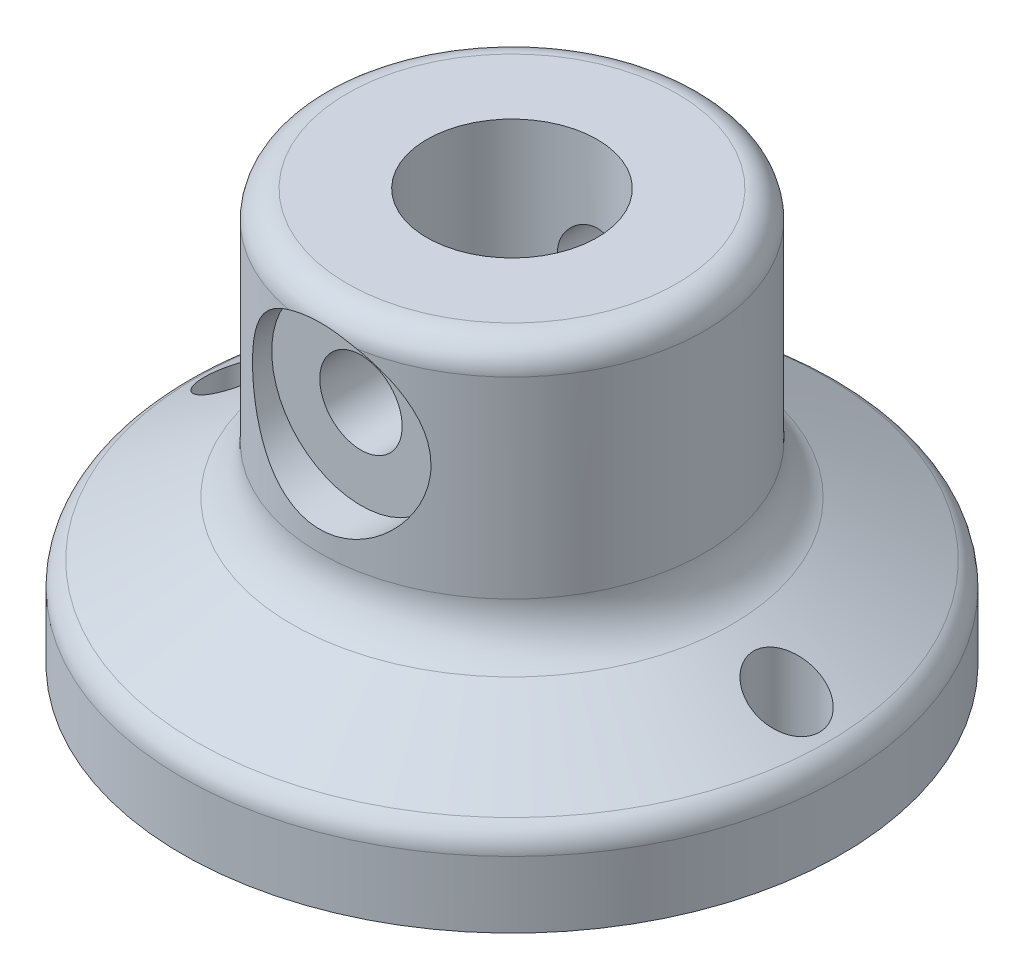
SolidWorks part; units mm, degrees
material "ABS"
ref_plane "Plan de face" through (0, 0, 0) normal (0, 0, 1) x (1, 0, 0)
ref_plane "Plan de dessus" through (0, 0, 0) normal (0, 1, 0) x (1, 0, 0)
ref_plane "Plan de droite" through (0, 0, 0) normal (1, 0, 0) x (0, 0, -1)
sketch "Esquisse1" plane through (0, 0, 0) normal (0, 0, 1) x (1, 0, 0)
  line L0 (0, 0) -> (0, 15) construction
  line L2 (3.1, 15) -> (3.1, 1)
  line L3 (4, 0) -> (12, 0)
  line L4 (12, 0) -> (12, 3)
  line L5 (12, 3) -> (8.0136, 5.2602)
  line L6 (7, 7) -> (7, 15)
  line L7 (7, 15) -> (3.1, 15)
  line L10 (3.1, 1) -> (4, 1)
  line L11 (4, 0) -> (4, 1)
  arc A0 (8.0136, 5.2602) -> (7, 7) centre (9, 7) cw
  dimension "D1" = 6.2
  dimension "D6" = 2
  dimension "D2" = 3
  dimension "D3" = 24
  dimension "D4" = 8
  dimension "D5" = 15
  dimension "D7" = 14
  dimension "D8" = 8
  dimension "D9" = 1
revolve "Révolution1" add sketch "Esquisse1" angle 360 about L0
fillet "Congé1" radius 1 2 edges at (0, 3, -12) (0, 15, -7)
sketch "Esquisse2" plane through (0, 0, 0) normal (0, -1, 0) x (1, 0, 0)
  line L0 (-10, 0) -> (10, 0) construction
  circle A0 centre (-10, 0) radius 1.2
  circle A1 centre (10, 0) radius 1.2
  dimension "D1" = 20
  dimension "D2" = 2.4
extrude "Enlèv. mat.-Extru.1" cut sketch "Esquisse2" against normal through all
hole_wizard "Chambrage pour vis à tête cylindrique à 6 pans creux (ou vis CHC) M31" positions "Esquisse3D1" profile "Esquisse5" counterbore size "M3" standard "Ansi Metric" end condition through all
sketch3d "Esquisse3D1"
  point P0 (0, 11, 7)
  dimension "D1" = 4
sketch "Esquisse5" plane through (0, 11, 7) normal (1, 0, 0) x (0, -1, 0)
  line L0 (0, 0) -> (0, 19)
  line L1 (0, 19) -> (1.2, 19)
  line L3 (1.2, 19) -> (1.2, 1.5)
  line L4 (1.2, 1.5) -> (3.25, 1.5)
  line L5 (3.25, 1.5) -> (3.25, 0)
  line L7 (3.25, 0) -> (0, 0)
  line L11 (0, -6.35) -> (0, 107.95) construction
  dimension "Diamètre du perçage jusqu'au prochain" = 2.4
  dimension "Profondeur du perçage jusqu'au prochain" = 19
  dimension "Diamètre du chambrage" = 6.5
  dimension "Profondeur du chambrage" = 1.5
sketch "Esquisse3" plane through (0, 0, 0) normal (0, 0, 1) x (1, 0, 0)
  line L0 (7, 15) -> (-7, 15) construction
  circle A0 centre (0, 11) radius 1.5
  dimension "D1" = 4
  dimension "D2" = 3
extrude "Enlèv. mat.-Extru.2" cut sketch "Esquisse3" along normal through all
